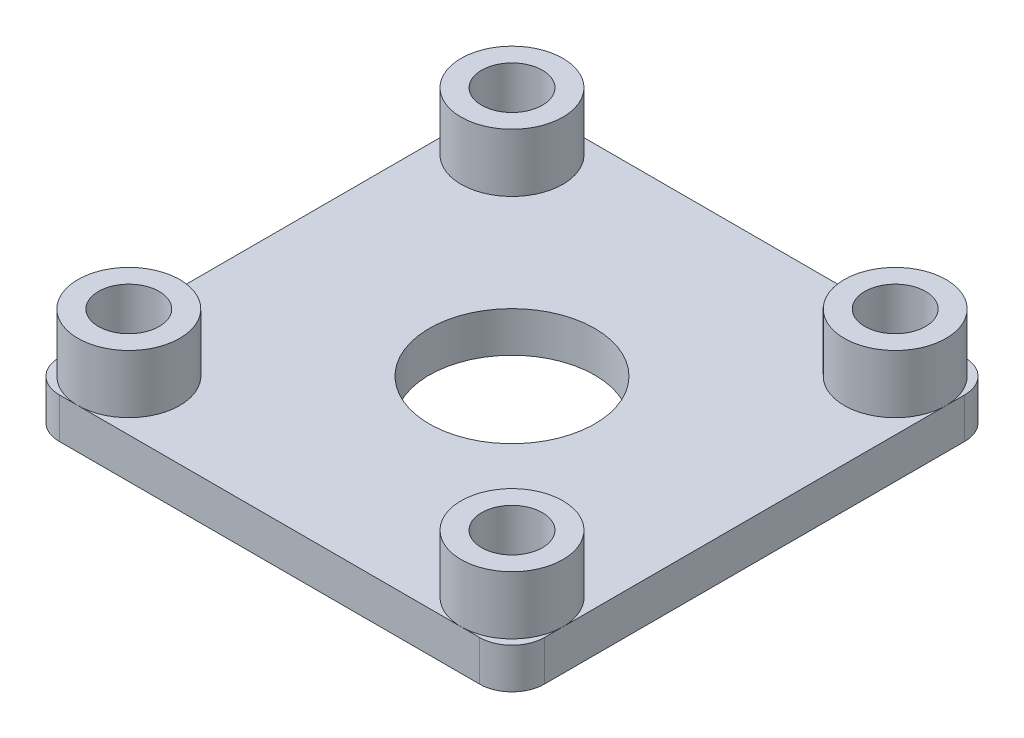
SolidWorks part; units mm, degrees
material "Alum Plate"
ref_plane "Front Plane" through (0, 0, 0) normal (0, 0, 1) x (1, 0, 0)
ref_plane "Top Plane" through (0, 0, 0) normal (0, 1, 0) x (1, 0, 0)
ref_plane "Right Plane" through (0, 0, 0) normal (1, 0, 0) x (0, 0, -1)
other "Bounding Box"
ref_plane "Default Plane" through (-8.9266, -12.7485, 0) normal (-0.1736, 0.9848, 0) x (0.9848, 0.1736, 0)
sketch "Sketch1" plane through (0, 0, 0) normal (0, 1, 0) x (1, 0, 0)
  line L0 (0, -12.5) -> (0, 12.5) construction
  line L1 (-14.5, 0) -> (0, 14.5) construction
  line L2 (-19.05, 19.05) -> (19.05, 19.05)
  line L3 (-19.05, 19.05) -> (-19.05, -19.05)
  line L4 (-19.05, -19.05) -> (19.05, -19.05)
  line L5 (19.05, 19.05) -> (19.05, -19.05)
  line L6 (-19.05, 19.05) -> (19.05, -19.05) construction
  line L7 (-19.05, -19.05) -> (19.05, 19.05) construction
  line L8 (8.8388, 8.8388) -> (-8.8388, 8.8388) construction
  line L9 (8.8388, 8.8388) -> (8.8388, -8.8388) construction
  line L10 (8.8388, -8.8388) -> (-8.8388, -8.8388) construction
  line L11 (-8.8388, 8.8388) -> (-8.8388, -8.8388) construction
  line L12 (8.8388, 8.8388) -> (-8.8388, -8.8388) construction
  line L13 (8.8388, -8.8388) -> (-8.8388, 8.8388) construction
  line L14 (-14.5, 0) -> (0, -14.5) construction
  line L15 (0, 14.5) -> (14.5, 0) construction
  line L16 (0, -14.5) -> (14.5, 0) construction
  line L17 (-14.5, 0) -> (14.5, 0) construction
  line L18 (0, 14.5) -> (0, -14.5) construction
  circle A0 centre (-15.24, 15.24) radius 1.3843 construction
  circle A1 centre (15.24, 15.24) radius 1.3843 construction
  circle A2 centre (15.24, -15.24) radius 1.3843 construction
  circle A3 centre (-15.24, -15.24) radius 1.3843 construction
  circle A4 centre (0, 0) radius 4
  circle A5 centre (8.8388, 8.8388) radius 1.5875
  circle A6 centre (8.8388, -8.8388) radius 1.5875
  circle A7 centre (-8.8388, -8.8388) radius 1.5875
  circle A8 centre (-8.8388, 8.8388) radius 1.5875
  circle A9 centre (-14.5, 0) radius 1.25
  circle A10 centre (0, 14.5) radius 1.25
  circle A11 centre (14.5, 0) radius 1.25
  circle A12 centre (0, -14.5) radius 1.25
  point P3 (0, 0)
  circle B0 centre (-9.8995, -9.8995) radius 1.2645 construction
  circle B1 centre (0, -8) radius 1.5875 construction
  circle B2 centre (0, 0) radius 4 construction
  circle B3 centre (9.8995, 9.8995) radius 1.2645 construction
  circle B4 centre (0, 8) radius 1.5875 construction
  circle B5 centre (9.8995, -9.8995) radius 1.2645 construction
  circle B6 centre (0, -12.5) radius 1.5875 construction
  circle B7 centre (-9.5, 0) radius 1.5875 construction
  circle B8 centre (-15.24, 15.24) radius 1.3843 construction
  circle B9 centre (15.24, 15.24) radius 1.3843 construction
  circle B10 centre (15.24, -15.24) radius 1.3843 construction
  circle B11 centre (-15.24, -15.24) radius 1.3843 construction
  circle B12 centre (9.5, 0) radius 1.5875 construction
  circle B13 centre (-9.8995, 9.8995) radius 1.2645 construction
  circle B14 centre (0, 12.5) radius 1.5875 construction
  dimension "D2" = 3.175
  dimension "D4" = 2.5
  dimension "D1" = 38.1
  dimension "D3" = 25
  dimension "D5" = 29
sketch_block_instance "Block-36mm gearbox motor block holes-1"
sketch_block "Block-36mm gearbox motor block holes"
extrude "Boss-Extrude1" add sketch "Sketch1" along normal mid plane 6.35
sketch "Sketch4" plane through (0, 0, 19.05) normal (0, 0, 1) x (1, 0, 0)
  line L0 (-5.5562, 0) -> (0, 0) construction
  line L1 (0, 0) -> (5.5562, 0) construction
  circle A0 centre (-5.5562, 0) radius 1.7272
  circle A1 centre (5.5562, 0) radius 1.7272
  dimension "D2" = 3.4544
  dimension "D1" = 11.1125
extrude "Cut-Extrude2" cut sketch "Sketch4" against normal blind 10.795
sketch "Sketch7" plane through (0, -3.175, 0) normal (0, -1, 0) x (1, 0, 0)
  line L0 (-19.05, 15.05) -> (-15.05, 15.05) construction
  line L1 (-19.05, -19.05) -> (-19.05, 19.05) construction
  line L2 (-15.05, 15.05) -> (-15.05, 19.05) construction
  line L3 (-19.05, 19.05) -> (19.05, 19.05) construction
  line L4 (0, 0) -> (-15.05, 15.05) construction
  line L5 (0, 0) -> (15.05, 15.05) construction
  circle A0 centre (-15.05, 15.05) radius 2.1526
  circle A1 centre (15.05, 15.05) radius 2.1527
  circle A2 centre (15.05, -15.05) radius 2.1527
  circle A3 centre (-15.05, -15.05) radius 2.1526
  dimension "D2" = 4.3053
  dimension "D1" = 30.1
  dimension "D4" = 90
  dimension "D3" = 4
extrude "Cut-Extrude3" cut sketch "Sketch7" against normal through all
pattern_circular "CirPattern1" count 4 over 360 about axis through (0, 0, 0) along (0, 1, 0) of "Cut-Extrude2"
ref_plane "Plane1" through (0, -32.512, 0) normal (0, -1, 0) x (-1, 0, 0)
sketch "Sketch6" plane through (0, -32.512, 0) normal (0, -1, 0) x (-1, 0, 0)
  line L0 (19.05, 19.05) -> (-19.05, 19.05) construction
  line L1 (19.05, 19.05) -> (19.05, -19.05) construction
  line L2 (19.05, -19.05) -> (-19.05, -19.05) construction
  line L3 (-19.05, 19.05) -> (-19.05, -19.05) construction
  line L12 (19.05, 19.05) -> (-19.05, 19.05)
  line L13 (19.05, 19.05) -> (19.05, -19.05)
  line L14 (19.05, -19.05) -> (-19.05, -19.05)
  line L15 (-19.05, 19.05) -> (-19.05, -19.05)
  circle A8 centre (0, 0) radius 6.5
  circle A17 centre (-15.05, 15.05) radius 2.1526
  circle A18 centre (15.05, 15.05) radius 2.1527
  circle A19 centre (15.05, -15.05) radius 2.1527
  circle A20 centre (-15.05, -15.05) radius 2.1526
  circle A21 centre (-15.05, 15.05) radius 2.1527 construction
  dimension "D2" = 13
extrude "Boss-Extrude2" add sketch "Sketch6" along normal blind 3.175 separate body
fillet "Fillet1" radius 2.54 4 edges at (-19.05, 0, 19.05) (-19.05, 0, -19.05) (19.05, 0, -19.05) (19.05, 0, 19.05)
fillet "Fillet2" radius 2.54 4 edges at (-19.05, -34.0995, 19.05) (-19.05, -34.0995, -19.05) (19.05, -34.0995, -19.05) (19.05, -34.0995, 19.05)
sketch "Sketch8" plane through (0, -32.512, 0) normal (0, 1, 0) x (1, 0, 0)
  line L0 (-16.51, 19.05) -> (16.51, 19.05) construction
  circle A0 centre (-15.05, 15.05) radius 2.3876
  circle A1 centre (-15.05, 15.05) radius 4
  dimension "D1" = 4.7752
extrude "Boss-Extrude3" add sketch "Sketch8" along normal offset from surface (4.572 mm away) 24.765 separate body up to face at (-15.05, -3.175, -17.2026)
pattern_circular "CirPattern2" count 4 over 360 about axis through (0, 0, 0) along (0, 1, 0) of bodies 110
delete or keep bodies "Body-Delete/Keep 1" [suppressed] type keep bodies bodies 108
delete or keep bodies "Body-Delete/Keep 2" [suppressed] type keep bodies bodies 107
delete or keep bodies "Body-Delete/Keep 3" [suppressed] bodies 113
delete or keep bodies "Body-Delete/Keep 4" type delete bodies bodies 107
